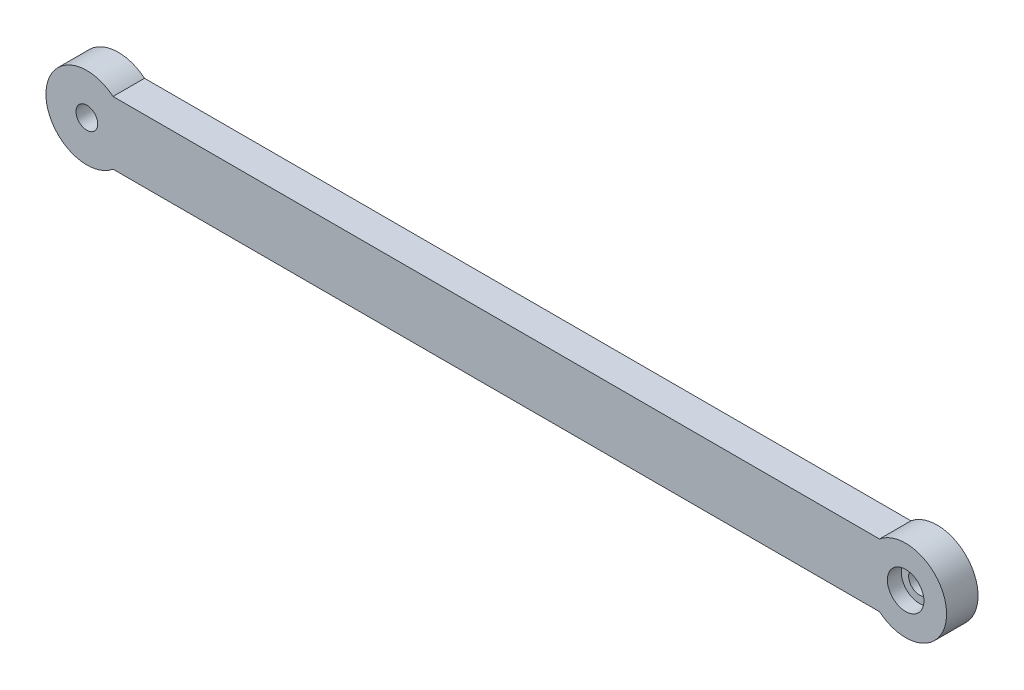
SolidWorks part; units mm, degrees
ref_plane "Front Plane" through (0, 0, 0) normal (0, 0, 1) x (1, 0, 0)
ref_plane "Top Plane" through (0, 0, 0) normal (0, 1, 0) x (1, 0, 0)
ref_plane "Right Plane" through (0, 0, 0) normal (1, 0, 0) x (0, 0, -1)
sketch "Sketch1" plane through (0, 0, 0) normal (0, 0, 1) x (1, 0, 0)
  line L0 (0, -5) -> (130, -5)
  line L1 (130, -5) -> (130, 5)
  line L2 (130, 5) -> (0, 5)
  line L3 (0, 5) -> (0, -5)
extrude "Boss-Extrude1" add sketch "Sketch1" along normal blind 5 from offset 3
sketch "Sketch2" plane through (0, 0, 0) normal (0, 0, 1) x (1, 0, 0)
  circle A0 centre (0, 0) radius 6.5
extrude "Boss-Extrude2" add sketch "Sketch2" along normal blind 5 from offset 3
sketch "Sketch3" plane through (0, 0, 0) normal (0, 0, 1) x (1, 0, 0)
  circle A0 centre (130, 0) radius 6.5
extrude "Boss-Extrude3" add sketch "Sketch3" along normal blind 5 from offset 3
sketch "Sketch4" plane through (0, 0, 0) normal (0, 0, 1) x (1, 0, 0)
  circle A0 centre (0, 0) radius 1.725
  circle A1 centre (130, 0) radius 1.725
extrude "Cut-Extrude1" cut sketch "Sketch4" against normal through all and the other way through all
sketch "Sketch5" plane through (0, 0, 0) normal (0, 0, 1) x (1, 0, 0)
  circle A0 centre (130, 0) radius 2.9
extrude "Cut-Extrude2" cut sketch "Sketch5" along normal blind 2.2 from offset 0.2
